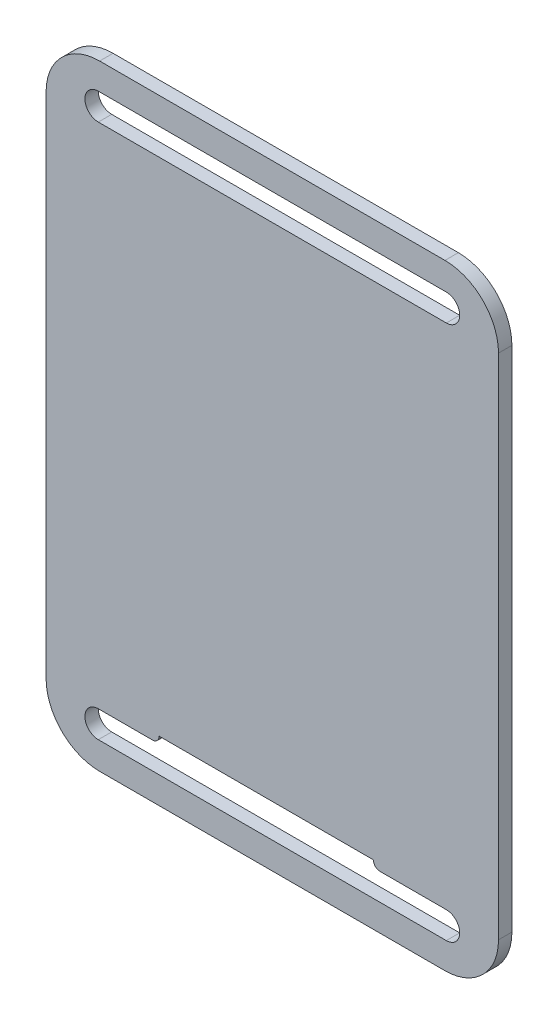
SolidWorks part; units mm, degrees
ref_plane "Front Plane" through (0, 0, 0) normal (0, 0, 1) x (1, 0, 0)
ref_plane "Top Plane" through (0, 0, 0) normal (0, 1, 0) x (1, 0, 0)
ref_plane "Right Plane" through (0, 0, 0) normal (1, 0, 0) x (0, 0, -1)
ref_plane "Plane1" through (0, 0, 0.6) normal (0, 0, -1) x (-1, 0, 0)
sketch "Sketch1" plane through (0, 0, 0.6) normal (0, 0, -1) x (-1, 0, 0)
  line L0 (-4, 45.96) -> (-29.8, 45.96)
  line L1 (-33.8, 41.96) -> (-33.8, 4)
  line L2 (-29.8, 0) -> (-4, 0)
  line L3 (0, 4) -> (0, 41.96)
  line L12 (-7.95, 4) -> (-3.9, 4)
  line L13 (-3.9, 2) -> (-29.9, 2)
  line L14 (-29.9, 4) -> (-24.95, 4)
  line L15 (-24.45, 4.5) -> (-8.45, 4.5)
  line L16 (-3.9, 41.96) -> (-29.9, 41.96)
  line L17 (-29.9, 43.96) -> (-3.9, 43.96)
  arc A0 (0, 41.96) -> (-4, 45.96) centre (-4, 41.96) ccw
  arc A1 (-29.8, 45.96) -> (-33.8, 41.96) centre (-29.8, 41.96) ccw
  arc A2 (-33.8, 4) -> (-29.8, 0) centre (-29.8, 4) ccw
  arc A3 (-4, 0) -> (0, 4) centre (-4, 4) ccw
  arc A20 (-8.45, 4.5) -> (-7.95, 4) centre (-7.95, 4.5) ccw
  arc A21 (-3.9, 4) -> (-3.9, 2) centre (-3.9, 3) cw
  arc A22 (-29.9, 2) -> (-29.9, 4) centre (-29.9, 3) cw
  arc A23 (-24.95, 4) -> (-24.45, 4.5) centre (-24.95, 4.5) ccw
  arc A24 (-3.9, 43.96) -> (-3.9, 41.96) centre (-3.9, 42.96) cw
  arc A25 (-29.9, 41.96) -> (-29.9, 43.96) centre (-29.9, 42.96) cw
extrude "Boss-Extrude1" add sketch "Sketch1" against normal blind 1
